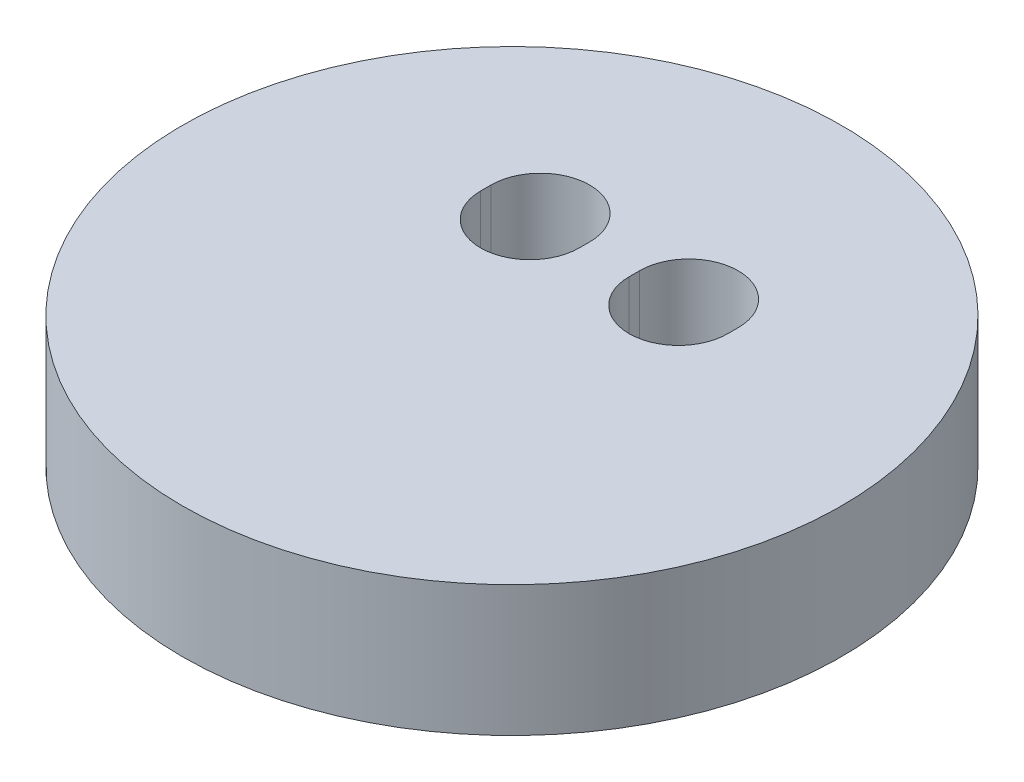
SolidWorks part; units mm, degrees
ref_plane "Front Plane" through (0, 0, 0) normal (0, 0, 1) x (1, 0, 0)
ref_plane "Top Plane" through (0, 0, 0) normal (0, 1, 0) x (1, 0, 0)
ref_plane "Right Plane" through (0, 0, 0) normal (1, 0, 0) x (0, 0, -1)
sketch "Sketch1" plane through (0, 0, 0) normal (0, 1, 0) x (1, 0, 0)
  circle A0 centre (0, 0) radius 12.36
  dimension "D1" = 24.72
extrude "Boss-Extrude1" add sketch "Sketch1" along normal blind 4.9
sketch "Sketch2" plane through (0, 4.9, 0) normal (0, 1, 0) x (1, 0, 0)
  line L0 (-2.785, 3.85) -> (-2.785, 3.46) construction
  line L1 (2.785, 3.85) -> (2.785, 3.46) construction
  line L2 (4.635, 3.85) -> (4.635, 3.46)
  line L3 (0.935, 3.85) -> (0.935, 3.46)
  line L4 (-0.935, 3.85) -> (-0.935, 3.46)
  line L5 (-4.635, 3.85) -> (-4.635, 3.46)
  line L6 (-2.785, 5.7) -> (2.785, 5.7) construction
  arc A3 (4.635, 3.85) -> (0.935, 3.85) centre (2.785, 3.85) ccw
  arc A4 (0.935, 3.46) -> (4.635, 3.46) centre (2.785, 3.46) ccw
  arc A5 (-0.935, 3.85) -> (-4.635, 3.85) centre (-2.785, 3.85) ccw
  arc A6 (-4.635, 3.46) -> (-0.935, 3.46) centre (-2.785, 3.46) ccw
  circle A7 centre (0, 0) radius 12.36 construction
  point P1 (-2.785, 3.655)
  point P2 (-4.635, 3.655)
  point P3 (-0.935, 3.655)
  point P8 (2.785, 3.655)
  point P14 (2.785, 5.7)
  point P15 (2.785, 1.61)
  point P16 (4.635, 3.655)
  point P17 (0.935, 3.655)
  point P20 (-2.785, 5.7)
  point P24 (-2.785, 1.61)
  point P29 (0, 5.7)
  dimension "D2" = 4.09
  dimension "D1" = 3.7
  dimension "D3" = 3.7
  dimension "D4" = 4.09
  dimension "D5" = 5.7
  dimension "D6" = 5.57
extrude "Cut-Extrude1" cut sketch "Sketch2" against normal through all
